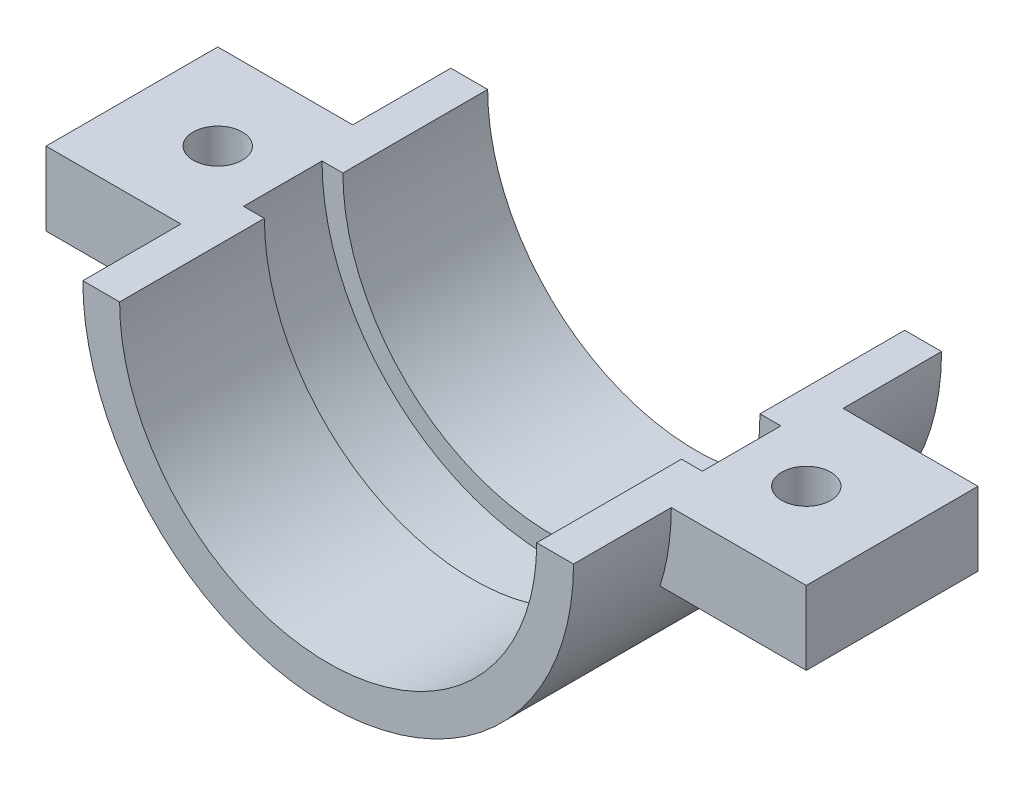
SolidWorks part; units mm, degrees
ref_plane "Front Plane" through (0, 0, 0) normal (0, 0, 1) x (1, 0, 0)
ref_plane "Top Plane" through (0, 0, 0) normal (0, 1, 0) x (1, 0, 0)
ref_plane "Right Plane" through (0, 0, 0) normal (1, 0, 0) x (0, 0, -1)
sketch "Sketch1" plane through (0, 0, 0) normal (0, 0, 1) x (1, 0, 0)
  line L0 (-10, 0) -> (-8.5, 0)
  line L1 (8.5, 0) -> (10, 0)
  arc A0 (-8.5, 0) -> (8.5, 0) centre (0, 0) ccw
  arc A1 (-10, 0) -> (10, 0) centre (0, 0) ccw
  dimension "D1" = 17
  dimension "D2" = 20
extrude "Boss-Extrude1" add sketch "Sketch1" along normal blind 15
sketch "Sketch2" plane through (0, 0, 0) normal (0, 1, 0) x (1, 0, 0)
  line L5 (-8.5, -15) -> (-8.5, 0) construction
  line L8 (8.5, -15) -> (8.5, 0) construction
  line L12 (-8.5, -7.5) -> (8.5, -7.5) construction
  line L13 (-8.5, -7.5) -> (-28.3179, -7.5) construction
  line L14 (-8.5, -4) -> (-15.5, -4)
  line L15 (-15.5, -4) -> (-15.5, -11)
  line L16 (-15.5, -11) -> (-8.5, -11)
  line L17 (-8.5, -11) -> (-8.5, -4)
  line L18 (-15.5, -7.5) -> (-12, -7.5) construction
  line L19 (8.5, -4.0149) -> (15.5, -4.0149)
  line L20 (15.5, -4.0149) -> (15.5, -11.0149)
  line L21 (15.5, -11.0149) -> (8.5, -11.0149)
  line L22 (8.5, -11.0149) -> (8.5, -4.0149)
  line L23 (15.5, -7.5149) -> (12, -7.5149) construction
  circle A0 centre (-12, -7.5) radius 1
  circle A1 centre (12, -7.5149) radius 1
  point P0 (-8.5, -3.9998)
  point P4 (-13.9756, -7.5)
  point P5 (-10, -11.0148)
  dimension "D5" = 3.5
  dimension "D6" = 2
  dimension "D4" = 2
  dimension "D1" = 7
  dimension "D2" = 7
  dimension "D3" = 3.5
extrude "Boss-Extrude2" add sketch "Sketch2" against normal blind 3
ref_plane "Plane1" through (0, 0, 7.5) normal (0, 0, -1) x (-1, 0, 0)
sketch "Sketch3" plane through (0, 0, 7.5) normal (0, 0, -1) x (-1, 0, 0)
  line L0 (-9.35, 0) -> (-8.5, 0)
  line L1 (8.5, 0) -> (9.35, 0)
  arc A0 (-8.5, 0) -> (8.5, 0) centre (0, 0) ccw
  arc A1 (-9.35, 0) -> (9.35, 0) centre (0, 0) ccw
  dimension "D1" = 18.7
extrude "Cut-Extrude1" cut sketch "Sketch3" against normal mid plane 3.2
